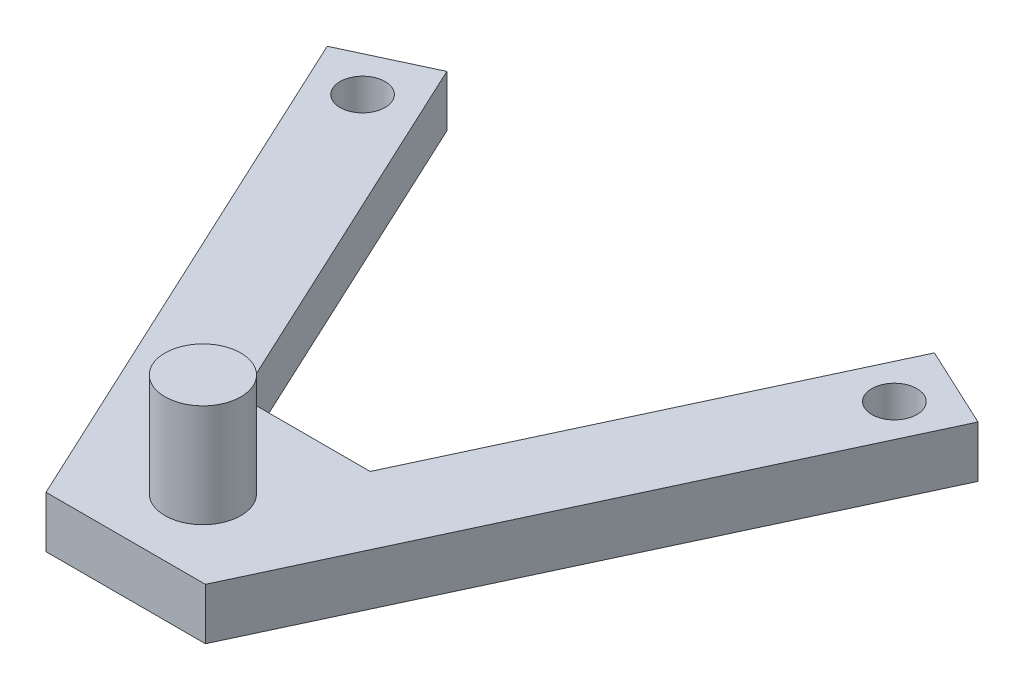
SolidWorks part; units mm, degrees
ref_plane "Front Plane" through (0, 0, 0) normal (0, 0, 1) x (1, 0, 0)
ref_plane "Top Plane" through (0, 0, 0) normal (0, 1, 0) x (1, 0, 0)
ref_plane "Right Plane" through (0, 0, 0) normal (1, 0, 0) x (0, 0, -1)
sketch "Sketch1" plane through (0, 0, 0) normal (0, 1, 0) x (1, 0, 0)
  line L1 (-40, -40) -> (40, -40)
  line L2 (-40, -40) -> (-40, 40)
  line L3 (-40, 40) -> (40, 40)
  line L4 (40, -40) -> (40, 40)
  line L5 (-40, -40) -> (40, 40) construction
  line L6 (-40, 40) -> (40, -40) construction
  point P0 (0, 0)
  dimension "D1" = 80
  dimension "D2" = 80
extrude "Boss-Extrude1" add sketch "Sketch1" along normal blind 4
sketch "Sketch2" plane through (0, 4, 0) normal (0, 1, 0) x (1, 0, 0)
  circle A0 centre (0, 0) radius 2.95
  dimension "D1" = 5.9
sketch "Sketch3" plane through (0, 4, 0) normal (0, 1, 0) x (1, 0, 0)
  line L0 (0, -2.2) -> (0, 2.2) construction
  line L1 (0, 0) -> (20.6669, 33.0739) construction
  circle A0 centre (20.6669, 33.0739) radius 1.75
  circle A1 centre (-20.6669, 33.0739) radius 1.75
  dimension "D1" = 3.5
  dimension "D2" = 39
  dimension "D3" = 32
extrude "Cut-Extrude2" cut sketch "Sketch3" against normal up to next
sketch "Sketch4" plane through (0, 4, 0) normal (0, 1, 0) x (1, 0, 0)
  line L0 (18.9464, 37.9082) -> (25.2906, 34.9498)
  line L1 (18.9464, 37.9082) -> (5, 8)
  line L2 (25.2906, 34.9498) -> (6.1953, -6)
  line L4 (0, -33.1519) -> (0, 33.1519) construction
  line L5 (-18.9464, 37.9082) -> (-25.2906, 34.9498)
  line L6 (-5, 8) -> (5, 8)
  line L7 (0, 8) -> (0, -6)
  line L8 (-6.1953, -6) -> (6.1953, -6)
  line L10 (-18.9464, 37.9082) -> (-5, 8)
  line L11 (-25.2906, 34.9498) -> (-6.1953, -6)
  point P9 (0, 0)
  line M8 (40, -40) -> (40, 40)
  line M9 (40, 40) -> (-40, 40)
  line M10 (-40, 40) -> (-40, -40)
  line M11 (-40, -40) -> (40, -40)
  dimension "D1" = 25
  dimension "D2" = 6
  dimension "D3" = 8
  dimension "D4" = 7
  dimension "D5" = 33
  dimension "D6" = 5
extrude "Cut-Extrude3" cut sketch "Sketch4" against normal blind 4 contours L4 L8 L11 L5 L10 L6 M11 M9 M10 | L4 L6 L1 L0 L2 L8 M11 M8 M9
extrude "Boss-Extrude2" add sketch "Sketch2" along normal blind 8
